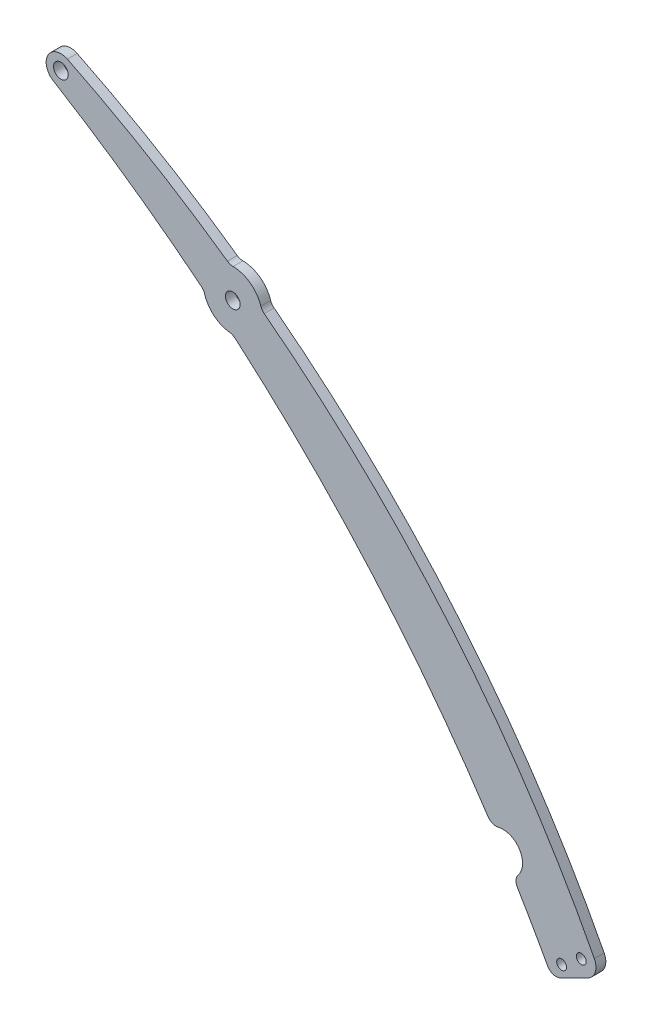
SolidWorks part; units mm, degrees
ref_plane "前视基准面" through (0, 0, 0) normal (0, 0, 1) x (1, 0, 0)
ref_plane "上视基准面" through (0, 0, 0) normal (0, 1, 0) x (1, 0, 0)
ref_plane "右视基准面" through (0, 0, 0) normal (1, 0, 0) x (0, 0, -1)
sketch "草图1" plane through (0, 0, 0) normal (0, 0, 1) x (1, 0, 0)
  line L0 (107.3025, -106.33) -> (101.7379, -109.1266)
  circle A0 centre (0, 0) radius 1.5
  arc A1 (1.322, 2.693) -> (-1.5587, -2.5633) centre (0, 0) ccw
  arc A2 (1.322, 2.693) -> (33.9065, -16.6345) centre (-104.4416, -212.7462) cw
  arc A3 (-1.5587, -2.5633) -> (28.5891, -23.732) centre (-147.0384, -241.8031) cw
  arc A4 (99.0818, -108.2932) -> (101.7379, -109.1266) centre (100.8398, -107.3396) ccw
  arc A5 (108.6186, -102.2685) -> (107.3025, -106.33) centre (105.9554, -103.6495) cw
  circle A6 centre (105.9554, -103.6495) radius 1
  circle A8 centre (101.9554, -106.6495) radius 1
  arc A9 (89.0821, -88.8702) -> (93.1109, -95.2778) centre (90, -92.7634) cw
  arc A10 (92.9522, -97.5653) -> (99.0818, -108.2932) centre (-147.0384, -241.8031) cw
  arc A11 (93.1109, -95.2778) -> (92.9522, -97.5653) centre (94.6664, -96.535) ccw
  arc A12 (89.0821, -88.8702) -> (86.9518, -88.022) centre (88.6231, -86.9235) cw
  arc A13 (29.251, -24.7173) -> (34.3572, -28.9655) centre (35, -23) ccw
  circle A14 centre (35, -23) radius 1.5
  arc A15 (41.4016, -22.1425) -> (108.6186, -102.2685) centre (-104.4416, -212.7462) cw
  arc A16 (35.4464, -29.4371) -> (86.9518, -88.022) centre (-147.0384, -241.8031) cw
  arc A17 (40.7127, -21.1656) -> (35.0445, -17.0002) centre (35, -23) ccw
  arc A18 (28.5891, -23.732) -> (29.251, -24.7173) centre (27.3347, -25.2897) cw
  arc A19 (35.4464, -29.4371) -> (34.3572, -28.9655) centre (34.1429, -30.954) ccw
  arc A20 (41.4016, -22.1425) -> (40.7127, -21.1656) centre (42.617, -20.5542) cw
  arc A21 (33.9065, -16.6345) -> (35.0445, -17.0002) centre (35.0594, -15.0002) ccw
  point P17 (92.1049, -96.1648)
  point P20 (100, -110)
  point P23 (110, -104.9743)
  point P38 (40.8647, -21.7329)
  dimension "D1" = 3
  dimension "D2" = 3
  dimension "D3" = 240
  dimension "D4" = 280
  dimension "D8" = 2
  dimension "D9" = 3
  dimension "D10" = 2
  dimension "D11" = 4
  dimension "D12" = 3
  dimension "D13" = 4
  dimension "D15" = 2
  dimension "D16" = 12
  dimension "D17" = 3
  dimension "D19" = 23
  dimension "D20" = 2
  dimension "D5" = 100
  dimension "D6" = 110
  dimension "D7" = 110
  dimension "D14" = 90
  dimension "D18" = 35
extrude "凸台-拉伸1" add sketch "草图1" along normal blind 2
move or copy body "实体-移动/复制1" [suppressed] bodies to move or copy 106
